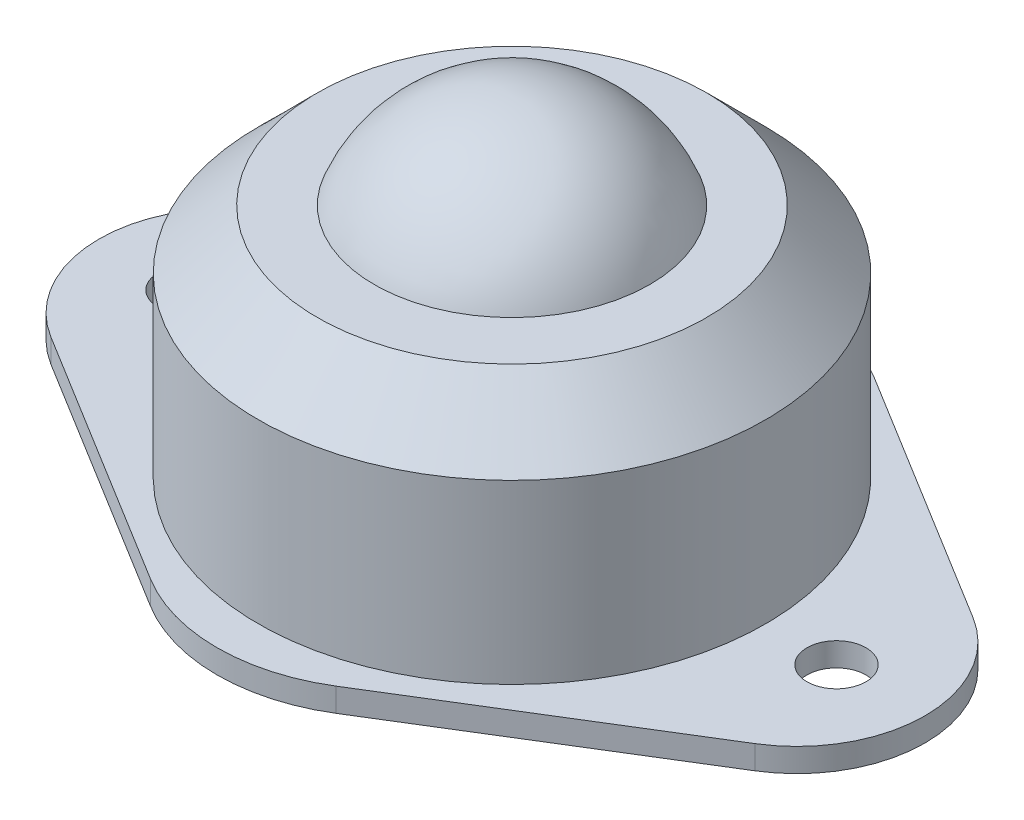
SolidWorks part; units mm, degrees
ref_plane "前视基准面" through (0, 0, 0) normal (0, 0, 1) x (1, 0, 0)
ref_plane "上视基准面" through (0, 0, 0) normal (0, 1, 0) x (1, 0, 0)
ref_plane "右视基准面" through (0, 0, 0) normal (1, 0, 0) x (0, 0, -1)
sketch "草图1" plane through (0, 0, 0) normal (0, 0, 1) x (1, 0, 0)
  line L0 (0, 0) -> (0, 8.9611) construction
  line L1 (-11.6694, 4.4805) -> (-16.5, 4.4805)
  line L2 (-21.5, -0.5195) -> (-21.5, -15.5)
  line L3 (-21.5, -15.5) -> (21.5, -15.5)
  line L4 (21.5, -15.5) -> (21.5, -0.5195)
  line L5 (16.5, 4.4805) -> (11.6694, 4.4805)
  line L6 (-16.5, 4.4805) -> (-21.5, -0.5195)
  line L7 (21.5, -0.5195) -> (16.5, 4.4805)
  line L8 (0, 12.5) -> (0, -15.5)
  arc A0 (11.6694, 4.4805) -> (-11.6694, 4.4805) centre (0, 0) ccw
  point P5 (-21.5, 4.4805)
  point P8 (21.5, 4.4805)
  point P14 (0, 12.5)
  dimension "D1" = 12.5
  dimension "D2" = 43
  dimension "D3" = 28
revolve "旋转2" add sketch "草图1" angle 360 about L0
sketch "草图2" plane through (0, -15.5, 0) normal (0, -1, 0) x (1, 0, 0)
  line L0 (55.7606, 0) -> (22.7865, 0) construction
  line L1 (0, 18.5302) -> (0, -7.3497) construction
  line L2 (-29.8413, 9.2362) -> (-7.8668, 22.7716)
  line L3 (-29.8413, -9.2362) -> (-7.8668, -22.7716)
  line L4 (29.8413, 9.2362) -> (7.8668, 22.7716)
  line L5 (29.8413, -9.2362) -> (7.8668, -22.7716)
  arc A0 (29.8413, -9.2362) -> (29.8413, 9.2362) centre (24.1522, 0) ccw
  arc A1 (-11.1803, 0) -> (0, -5) centre (0, 10) ccw construction
  arc A2 (-29.8413, -9.2362) -> (-29.8413, 9.2362) centre (-24.1522, 0) cw
  arc A3 (7.8668, -22.7716) -> (-7.8668, -22.7716) centre (0, -10) cw
  arc A4 (-7.8668, 22.7716) -> (-11.1803, 0) centre (0, 10) ccw construction
  arc A5 (7.8668, 22.7716) -> (-7.8668, 22.7716) centre (0, 10) ccw
  arc A6 (11.1803, 0) -> (7.8668, 22.7716) centre (0, 10) ccw construction
  arc A7 (0, -5) -> (11.1803, 0) centre (0, 10) ccw construction
  arc A8 (0, 5) -> (11.1803, 0) centre (0, -10) cw construction
  arc A9 (11.1803, 0) -> (7.8668, -22.7716) centre (0, -10) cw construction
  arc A10 (-11.1803, 0) -> (0, 5) centre (0, -10) cw construction
  arc A11 (-7.8668, -22.7716) -> (-11.1803, 0) centre (0, -10) cw construction
  arc A12 (13.3045, 0) -> (29.8413, -9.2362) centre (24.1522, 0) ccw construction
  arc A13 (29.8413, 9.2362) -> (13.3045, 0) centre (24.1522, 0) ccw construction
  arc A14 (-29.8413, 9.2362) -> (-13.3045, 0) centre (-24.1522, 0) cw construction
  arc A15 (-13.3045, 0) -> (-29.8413, -9.2362) centre (-24.1522, 0) cw construction
  circle A16 centre (-27.5, 0) radius 2.5
  circle A17 centre (27.5, 0) radius 2.5
  dimension "D1" = 35
  dimension "D2" = 21.6955
  dimension "D4" = 30
  dimension "D5" = 5
  dimension "D3" = 10
  dimension "D6" = 27.5
extrude "凸台-拉伸1" add sketch "草图2" along normal blind 2
